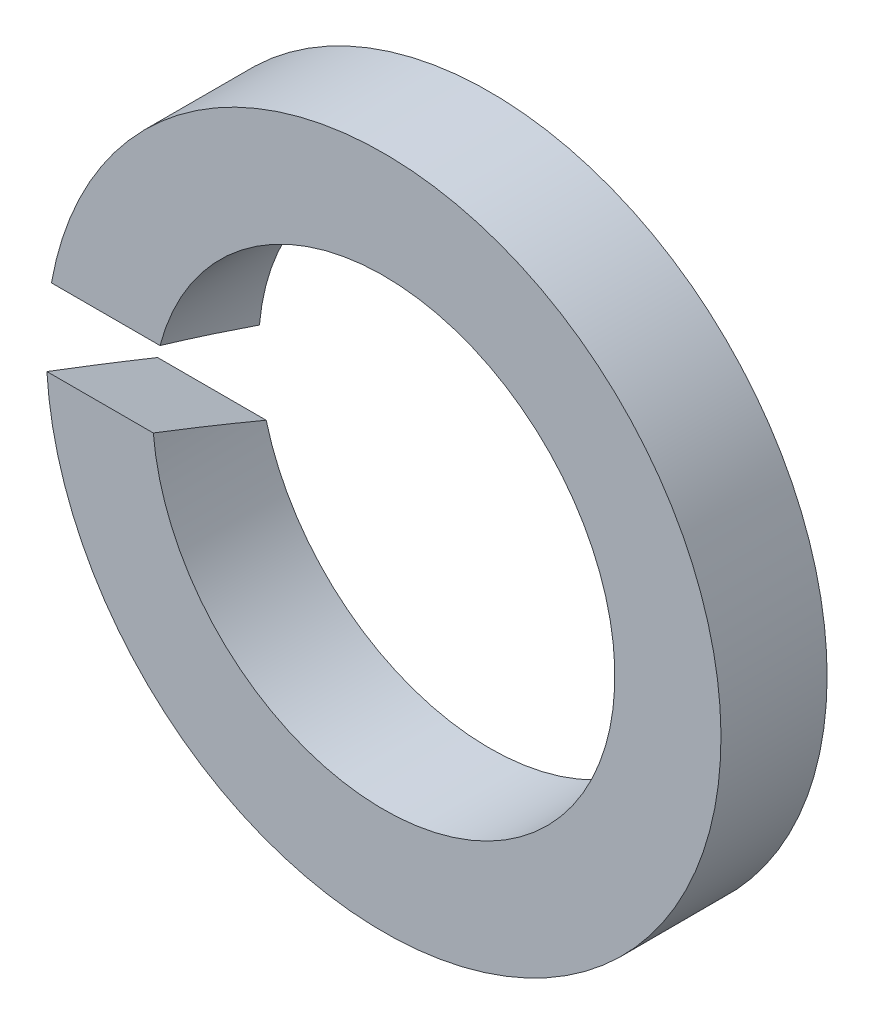
SolidWorks part; units mm, degrees
material "Сталь 45 ГОСТ 1050-88"
ref_plane "Плоскость1" through (0, 0, 0) normal (0, 0, 1) x (1, 0, 0)
ref_plane "Плоскость2" through (0, 0, 0) normal (0, 1, 0) x (1, 0, 0)
ref_plane "Плоскость3" through (0, 0, 0) normal (1, 0, 0) x (0, 0, -1)
sketch "Эскиз1" plane through (0, 0, 0) normal (0, 0, 1) x (1, 0, 0)
  circle A0 centre (0, 0) radius 3.05
  circle A1 centre (0, 0) radius 4.45
  dimension "d" = 6.1
  dimension "b" = 1.4
extrude "Вытянуть1" add sketch "Эскиз1" along normal blind 1.4
sketch "Эскиз2" plane through (0, 0, 0) normal (1, 0, 0) x (0, 0, -1)
  line L0 (0, 0) -> (-1.4, 0) construction
  line L1 (-1.4, 4.45) -> (-1.4, -4.45) construction
  line L2 (0, 0.2667) -> (-1.4, 0.7762)
  line L3 (0, -4.45) -> (0, 4.45) construction
  line L4 (0, -0.7762) -> (-1.4, -0.2667)
  line L5 (0, 0.2667) -> (0, 0)
  line L6 (-1.4, 0) -> (-1.4, -0.2667)
  line L7 (-1.4, 0.7762) -> (-1.4, 0)
  line L8 (0, 0) -> (0, -0.7762)
  dimension "_" = 70
  dimension "m" = 0.98
extrude "Вырез-Вытянуть1" cut sketch "Эскиз2" against normal through all
equation "\"D1@Вытянуть1\" = \"b@Эскиз1\""
